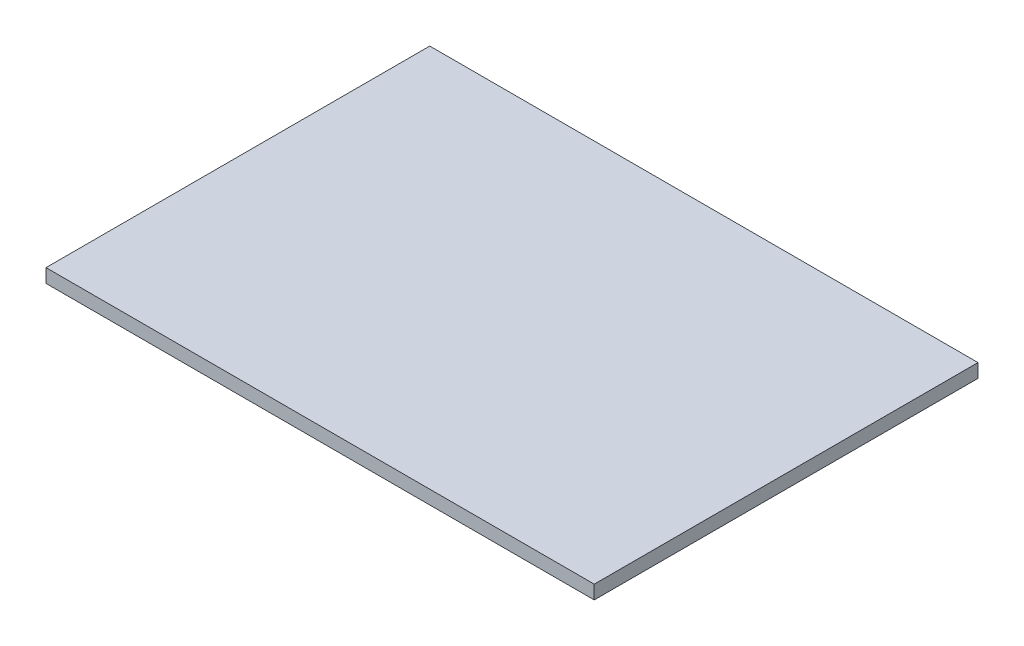
SolidWorks part; units mm, degrees
ref_plane "Front Plane" through (0, 0, 0) normal (0, 0, 1) x (1, 0, 0)
ref_plane "Top Plane" through (0, 0, 0) normal (0, 1, 0) x (1, 0, 0)
ref_plane "Right Plane" through (0, 0, 0) normal (1, 0, 0) x (0, 0, -1)
sketch "Sketch1" plane through (0, 0, 0) normal (0, 1, 0) x (1, 0, 0)
  line L1 (0, 0) -> (200, 0)
  line L2 (0, 0) -> (0, -140)
  line L3 (0, -140) -> (200, -140)
  line L4 (200, 0) -> (200, -140)
  dimension "D1" = 140
  dimension "D2" = 200
extrude "Boss-Extrude1" add sketch "Sketch1" along normal blind 5
